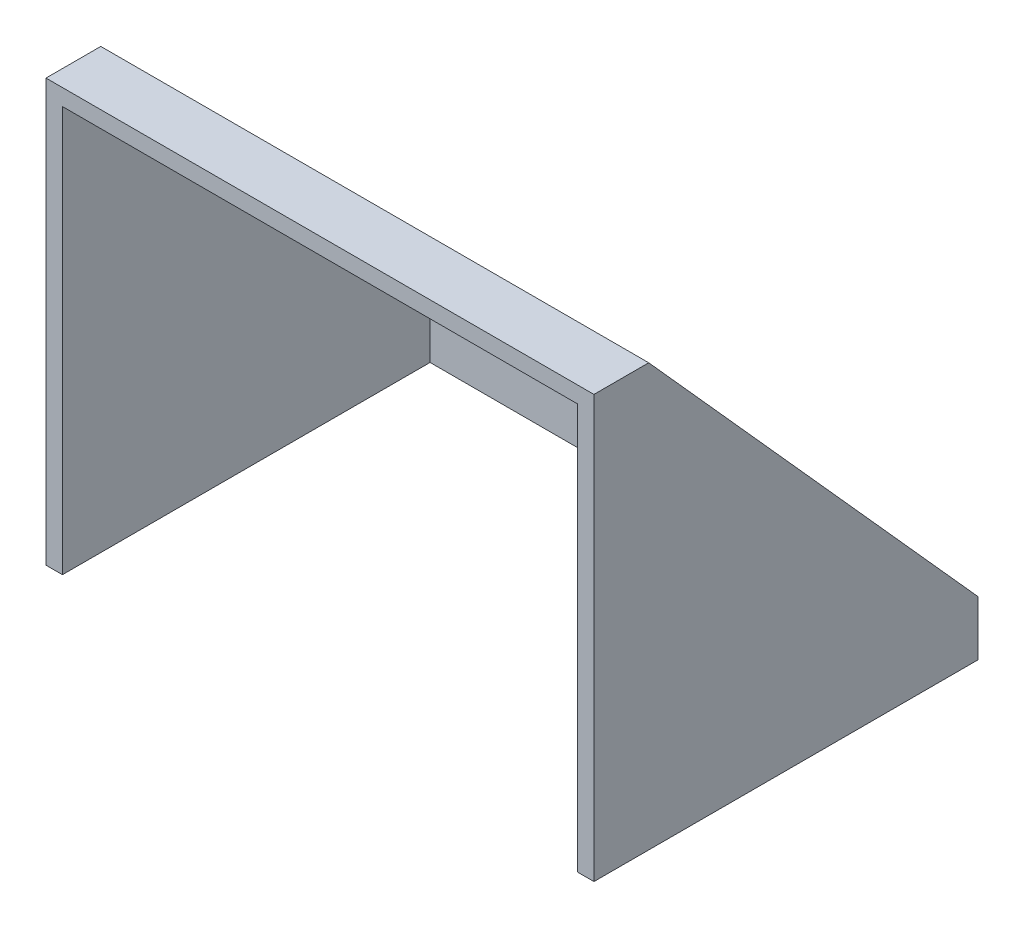
SolidWorks part; units mm, degrees
ref_plane "Plano frontal" through (0, 0, 0) normal (0, 0, 1) x (1, 0, 0)
ref_plane "Plano superior" through (0, 0, 0) normal (0, 1, 0) x (1, 0, 0)
ref_plane "Plano direito" through (0, 0, 0) normal (1, 0, 0) x (0, 0, -1)
sketch "Esboço2" plane through (0, 0, 0) normal (1, 0, 0) x (0, 0, -1)
  line L0 (0, 0) -> (70.0916, 0)
  line L1 (70.0916, 0) -> (70.0916, 10)
  line L2 (70.0916, 10) -> (10, 77)
  line L3 (10, 77) -> (0, 77)
  line L4 (0, 77) -> (0, 0)
  dimension "D1" = 90
  dimension "D2" = 10
  dimension "D3" = 10
  dimension "D4" = 77
extrude "Ressalto-extrusão1" add sketch "Esboço2" along normal mid plane 100
shell "Casca1" thickness 3
sketch "Esboço4" plane through (0, 39.2973, -43.8151) normal (0, 0.6677, -0.7444) x (1, 0, 0)
  line L0 (50, -50.6454) -> (-50, -50.6454) construction
  line L1 (39.5, -38.6454) -> (-39.5, -38.6454)
  line L2 (39.5, -38.6454) -> (39.5, 12.9546)
  line L3 (39.5, 12.9546) -> (-39.5, 12.9546)
  line L4 (-39.5, -38.6454) -> (-39.5, 12.9546)
  line L5 (39.5, -38.6454) -> (-39.5, 12.9546) construction
  line L6 (39.5, 12.9546) -> (-39.5, -38.6454) construction
  line L8 (44, 19.8546) -> (-44, 19.8546) construction
  line L9 (44, 19.8546) -> (44, -45.1454) construction
  line L10 (44, -45.1454) -> (-44, -45.1454) construction
  line L11 (-44, 19.8546) -> (-44, -45.1454) construction
  line L12 (44, 19.8546) -> (-44, -45.1454) construction
  line L13 (44, -45.1454) -> (-44, 19.8546) construction
  circle A0 centre (-44, 19.8546) radius 1.6
  circle A1 centre (-44, -45.1454) radius 1.6
  circle A2 centre (44, -45.1454) radius 1.6
  circle A3 centre (44, 19.8546) radius 1.6
  circle A4 centre (-37.5, 30.6546) radius 5
  circle A5 centre (36.75, 28.0546) radius 3
  circle A6 centre (-3.8, 31.0546) radius 2.5
  point P0 (0, -12.8454)
  point P9 (0, -12.6454)
  dimension "D7" = 3.2
  dimension "D11" = 10
  dimension "D14" = 6
  dimension "D16" = 5
  dimension "D1" = 51.6
  dimension "D2" = 79
  dimension "D3" = 12
  dimension "D4" = 65
  dimension "D5" = 88
  dimension "D6" = 6.5
  dimension "D8" = 75.8
  dimension "D9" = 6.5
  dimension "D10" = 7.25
  dimension "D12" = 76.2
  dimension "D13" = 40.2
  dimension "D15" = 8.2
extrude "Corte-extrusão1" cut sketch "Esboço4" against normal up to surface (3 mm away) up to face at (0, 41.4259, -37.8762)
